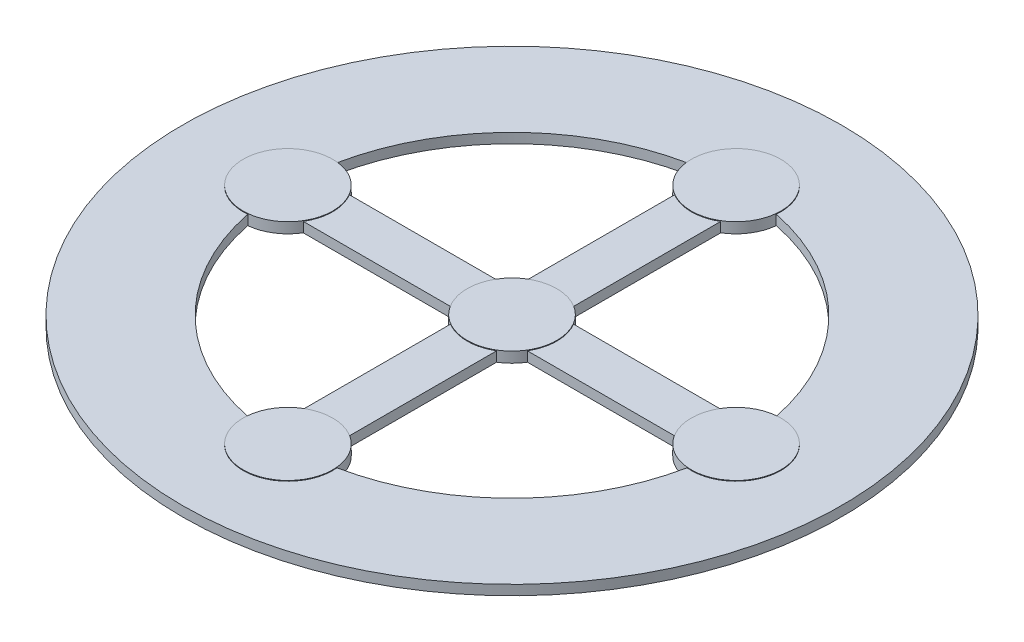
SolidWorks part; units mm, degrees
material "6061-T6 (SS)"
ref_plane "Front Plane" through (0, 0, 0) normal (0, 0, 1) x (1, 0, 0)
ref_plane "Top Plane" through (0, 0, 0) normal (0, 1, 0) x (1, 0, 0)
ref_plane "Right Plane" through (0, 0, 0) normal (1, 0, 0) x (0, 0, -1)
sketch "Sketch2" plane through (0, 0, 0) normal (0, 1, 0) x (1, 0, 0)
  circle A0 centre (0, 0) radius 550
  dimension "D1" = 1100
extrude "Boss-Extrude1" add sketch "Sketch2" along normal blind 15
sketch "Sketch3" plane through (0, 15, 0) normal (0, 1, 0) x (1, 0, 0)
  line L2 (0, 0) -> (0, 68) construction
  line L16 (0, 150) -> (0, 190) construction
  line L17 (-35, 58.3009) -> (-35, 281.6991)
  line L18 (35, 281.6991) -> (35, 58.3009)
  line L19 (58.3009, 35) -> (281.6991, 35)
  line L20 (281.6991, -35) -> (58.3009, -35)
  line L21 (35, -58.3009) -> (35, -281.6991)
  line L22 (-35, -281.6991) -> (-35, -58.3009)
  line L23 (-58.3009, -35) -> (-281.6991, -35)
  line L24 (-281.6991, 35) -> (-58.3009, 35)
  arc A0 (-58.3009, -35) -> (-35, -58.3009) centre (0, 0) ccw
  circle A15 centre (0, 0) radius 500
  arc A23 (35, 281.6991) -> (67.6591, 333.2) centre (0, 340) ccw
  circle A25 centre (0, 340) radius 150 construction
  circle A27 centre (0, 0) radius 150 construction
  arc A28 (281.6991, -35) -> (333.2, -67.6591) centre (340, 0) ccw
  arc A29 (-35, -281.6991) -> (-67.6591, -333.2) centre (0, -340) ccw
  arc A30 (-281.6991, 35) -> (-333.2, 67.6591) centre (-340, 0) ccw
  arc A32 (333.2, 67.6591) -> (67.6591, 333.2) centre (0, 0) ccw
  arc A33 (333.2, 67.6591) -> (281.6991, 35) centre (340, 0) ccw
  arc A34 (67.6591, -333.2) -> (35, -281.6991) centre (0, -340) ccw
  arc A35 (67.6591, -333.2) -> (333.2, -67.6591) centre (0, 0) ccw
  arc A36 (-333.2, -67.6591) -> (-281.6991, -35) centre (-340, 0) ccw
  arc A37 (-333.2, -67.6591) -> (-67.6591, -333.2) centre (0, 0) ccw
  arc A38 (-67.6591, 333.2) -> (-35, 281.6991) centre (0, 340) ccw
  arc A39 (-67.6591, 333.2) -> (-333.2, 67.6591) centre (0, 0) ccw
  arc A40 (35, -58.3009) -> (58.3009, -35) centre (0, 0) ccw
  arc A41 (58.3009, 35) -> (35, 58.3009) centre (0, 0) ccw
  arc A42 (-35, 58.3009) -> (-58.3009, 35) centre (0, 0) ccw
  point P28 (0, 0)
  point P33 (0, 0)
  point P43 (0, 0)
  point P53 (0, 0)
  dimension "D1" = 136
  dimension "D2" = 300
  dimension "D3" = 40
  dimension "D5" = 1000
  dimension "D4" = 70
  dimension "D6" = 4
extrude "Cut-Extrude1" cut sketch "Sketch3" against normal blind 30 flip side to cut
sketch "Sketch7" [suppressed] plane through (0, 15, -15) normal (0, -1, 0) x (1, 0, 0)
  line L2 (0, 0) -> (0, 68) construction
  line L16 (0, 150) -> (0, 190) construction
  line L17 (-35, 58.3009) -> (-35, 281.6991)
  line L18 (35, 281.6991) -> (35, 58.3009)
  circle A0 centre (0, 0) radius 68
  circle A15 centre (0, 0) radius 500
  arc A23 (35, 281.6991) -> (-35, 281.6991) centre (0, 340) ccw
  circle A25 centre (0, 340) radius 150 construction
  circle A27 centre (0, 0) radius 150 construction
  point P28 (0, 0)
  point P43 (0, 0)
  point P53 (0, 0)
  dimension "D1" = 136
  dimension "D2" = 300
  dimension "D3" = 40
  dimension "D5" = 1000
  dimension "D4" = 70
sketch "Sketch4" plane through (0, 15, 0) normal (0, 1, 0) x (1, 0, 0)
  circle A0 centre (0, 340) radius 68
  arc A1 (35, 281.6991) -> (67.6591, 333.2) centre (0, 340) ccw construction
extrude "Boss-Extrude2" add sketch "Sketch4" along normal blind 1
pattern_circular "CirPattern1" count 4 over 360 about axis through (0, 15, 0) along (0, 1, 0) of "Boss-Extrude2"
sketch "Sketch5" plane through (0, 15, 0) normal (0, 1, 0) x (1, 0, 0)
  circle A0 centre (0, 0) radius 68
  arc A2 (58.3009, 35) -> (35, 58.3009) centre (0, 0) ccw construction
extrude "Boss-Extrude3" add sketch "Sketch5" along normal blind 1
